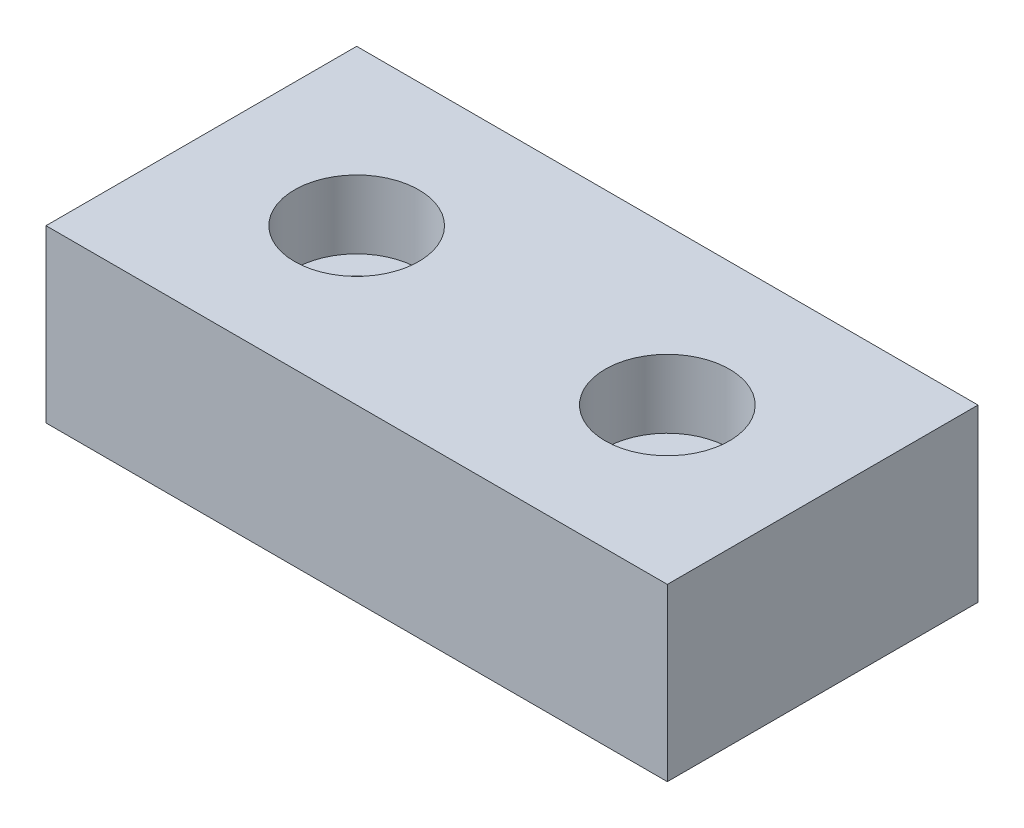
SolidWorks part; units mm, degrees
material "ABS"
ref_plane "Front Plane" through (0, 0, 0) normal (0, 0, 1) x (1, 0, 0)
ref_plane "Top Plane" through (0, 0, 0) normal (0, 1, 0) x (1, 0, 0)
ref_plane "Right Plane" through (0, 0, 0) normal (1, 0, 0) x (0, 0, -1)
sketch "Sketch1" plane through (0, 0, 0) normal (0, 1, 0) x (1, 0, 0)
  line L1 (0, 0) -> (40, 0)
  line L2 (0, 0) -> (0, 20)
  line L3 (0, 20) -> (40, 20)
  line L4 (40, 0) -> (40, 20)
  dimension "D1" = 20
  dimension "D2" = 40
extrude "Boss-Extrude1" add sketch "Sketch1" along normal blind 11
sketch "Sketch2" plane through (0, 11, 0) normal (0, 1, 0) x (1, 0, 0)
  line L0 (0, 0) -> (0, 20)
  line L1 (0, 20) -> (40, 20)
  line L2 (40, 20) -> (40, 15)
  line L3 (40, 0) -> (40, 20) construction
  line L4 (40, 15) -> (5, 15)
  line L5 (0, 0) -> (5, 0)
  line L6 (0, 0) -> (40, 0) construction
  line L7 (5, 0) -> (5, 15)
  dimension "D1" = 5
  dimension "D2" = 5
hole_wizard "CBORE for M4 Hex Socket Head Cap Screw1" positions "Sketch3" profile "Sketch4" counterbore size "M4" standard "ISO" end condition through all
sketch "Sketch3" plane through (0, 11, 0) normal (0, 1, 0) x (1, 0, 0)
  line L0 (0, 0) -> (40, 0) construction
  line L2 (0, 0) -> (0, 20) construction
  line L3 (40, 0) -> (40, 20) construction
  point P0 (10, 10)
  point P2 (30, 10)
  dimension "D1" = 10
  dimension "D2" = 10
  dimension "D3" = 10
  dimension "D4" = 10
sketch "Sketch4" plane through (10, 11, -10) normal (1, 0, 0) x (0, 0, 1)
  line L0 (0, 0) -> (0, 11)
  line L1 (0, 11) -> (2.25, 11)
  line L3 (2.25, 11) -> (2.25, 4.4)
  line L4 (2.25, 4.4) -> (4, 4.4)
  line L5 (4, 4.4) -> (4, 0)
  line L7 (4, 0) -> (0, 0)
  line L11 (0, -6.35) -> (0, 107.95) construction
  dimension "Thru Hole Dia." = 4.5
  dimension "Thru Hole Depth" = 11
  dimension "C'Bore Dia." = 8
  dimension "C'Bore Depth" = 4.4
mirror "Mirror3" [suppressed]
delete or keep bodies "Body-Delete/Keep 1" [suppressed] type delete bodies bodies 102
